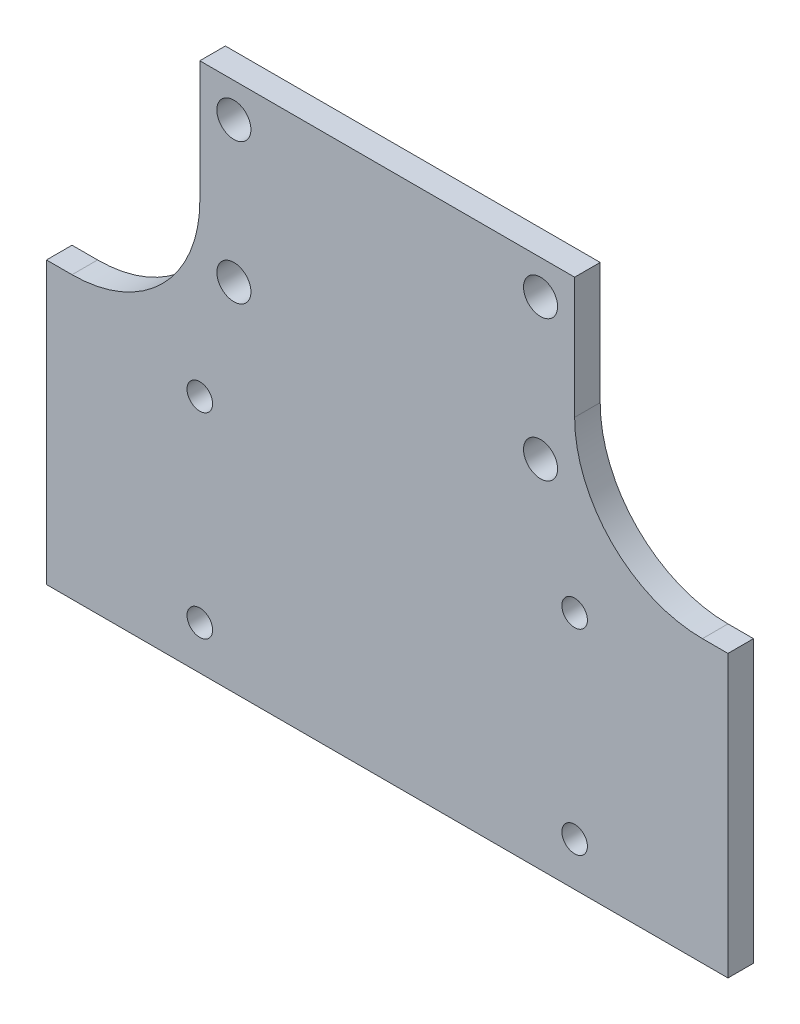
SolidWorks part; units mm, degrees
material "Thornel Mat VMA"
ref_plane "前视基准面" through (0, 0, 0) normal (0, 0, 1) x (1, 0, 0)
ref_plane "上视基准面" through (0, 0, 0) normal (0, 1, 0) x (1, 0, 0)
ref_plane "右视基准面" through (0, 0, 0) normal (1, 0, 0) x (0, 0, -1)
sketch "草图1" plane through (0, 0, 0) normal (0, 0, 1) x (1, 0, 0)
  line L0 (0, 0) -> (0, 68.6721) construction
  line L1 (40, 0) -> (-40, 0)
  line L2 (-40, 0) -> (-40, 33)
  line L3 (40, 0) -> (40, 33)
  line L4 (-40, 33) -> (-22, 33)
  line L5 (40, 33) -> (22, 33)
  line L6 (-22, 33) -> (-22, 62.25)
  line L7 (22, 33) -> (22, 62.25)
  line L8 (-22, 62.25) -> (22, 62.25)
  point P12 (0, 62.25)
  dimension "D1" = 62.25
  dimension "D2" = 80
  dimension "D3" = 44
  dimension "D4" = 33
extrude "凸台-拉伸1" add sketch "草图1" along normal blind 3
sketch "草图2" plane through (0, 0, 3) normal (0, 0, 1) x (1, 0, 0)
  line L0 (0, 62.25) -> (0, 0) construction
  line L1 (22, 62.25) -> (-22, 62.25) construction
  line L3 (-18, 58.25) -> (18, 58.25) construction
  line L4 (-18, 58.25) -> (-18, 41.75) construction
  line L5 (-18, 41.75) -> (18, 41.75) construction
  line L6 (18, 58.25) -> (18, 41.75) construction
  line L7 (-18, 58.25) -> (18, 41.75) construction
  line L8 (-18, 41.75) -> (18, 58.25) construction
  circle A0 centre (-18, 58.25) radius 2
  circle A1 centre (-18, 41.75) radius 2
  circle A2 centre (18, 41.75) radius 2
  circle A3 centre (18, 58.25) radius 2
  point P5 (0, 50)
  dimension "D4" = 4
  dimension "D1" = 36
  dimension "D2" = 16.5
  dimension "D3" = 12.25
extrude "切除-拉伸1" cut sketch "草图2" against normal through all
sketch "草图3" plane through (0, 0, 3) normal (0, 0, 1) x (1, 0, 0)
  line L0 (0, 62.25) -> (0, 0) construction
  line L1 (22, 62.25) -> (-22, 62.25) construction
  line L3 (-22, 28.125) -> (22, 28.125) construction
  line L4 (-22, 28.125) -> (-22, 5.125) construction
  line L5 (-22, 5.125) -> (22, 5.125) construction
  line L6 (22, 28.125) -> (22, 5.125) construction
  line L7 (-22, 28.125) -> (22, 5.125) construction
  line L8 (-22, 5.125) -> (22, 28.125) construction
  circle A1 centre (-22, 28.125) radius 1.5
  circle A2 centre (22, 28.125) radius 1.5
  circle A3 centre (22, 5.125) radius 1.5
  circle A4 centre (-22, 5.125) radius 1.5
  point P5 (0, 16.625)
  dimension "D4" = 3
  dimension "D1" = 23
  dimension "D2" = 44
  dimension "D3" = 45.625
extrude "切除-拉伸2" cut sketch "草图3" against normal through all
fillet "圆角1" radius 15 2 edges at (22, 33, 1.5) (-22, 33, 1.5)
